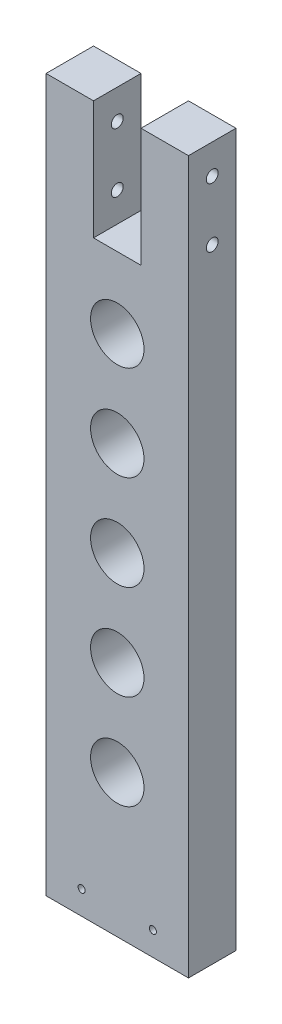
SolidWorks part; units mm, degrees
material "Kiefer"
ref_plane "Ebene vorne" through (0, 0, 0) normal (0, 0, 1) x (1, 0, 0)
ref_plane "Ebene oben" through (0, 0, 0) normal (0, 1, 0) x (1, 0, 0)
ref_plane "Ebene rechts" through (0, 0, 0) normal (1, 0, 0) x (0, 0, -1)
sketch "Skizze1" plane through (0, 0, 0) normal (0, 1, 0) x (1, 0, 0)
  line L1 (-30, 10) -> (30, 10)
  line L2 (-30, 10) -> (-30, -10)
  line L3 (-30, -10) -> (30, -10)
  line L4 (30, 10) -> (30, -10)
  line L5 (-30, 10) -> (30, -10) construction
  line L6 (-30, -10) -> (30, 10) construction
  point P0 (0, 0)
  dimension "D1" = 60
  dimension "D2" = 20
extrude "Aufsatz-Linear austragen1" add sketch "Skizze1" along normal blind 300
sketch "Skizze2" plane through (0, 0, 10) normal (0, 0, 1) x (1, 0, 0)
  line L0 (-30, 300) -> (30, 300) construction
  line L1 (-10, 300) -> (10, 300)
  line L2 (-10, 300) -> (-10, 250)
  line L3 (-10, 250) -> (10, 250)
  line L4 (10, 300) -> (10, 250)
  point P6 (0, 300)
  dimension "D1" = 20
  dimension "D2" = 50
extrude "Schnitt-Linear austragen1" cut sketch "Skizze2" against normal through all
sketch "Skizze3" plane through (0, 0, 10) normal (0, 0, 1) x (1, 0, 0)
  line L0 (0, 0) -> (0, 220) construction
  line L1 (-10, 250) -> (10, 250) construction
  circle A0 centre (0, 220) radius 11.25
  circle A1 centre (0, 180) radius 11.25
  circle A2 centre (0, 140) radius 11.25
  circle A3 centre (0, 100) radius 11.25
  circle A4 centre (0, 60) radius 11.25
  dimension "D1" = 22.5
  dimension "D2" = 30
  dimension "D3" = 40
  dimension "D4" = 80
  dimension "D5" = 120
  dimension "D6" = 160
extrude "Schnitt-Linear austragen2" cut sketch "Skizze3" against normal blind 300
sketch "Skizze7" plane through (0, 0, 10) normal (0, 0, 1) x (1, 0, 0)
  line L0 (-30, 300) -> (-30, 0) construction
  line L1 (-30, 20) -> (0, 20) construction
  line L2 (-30, 20) -> (-30, 0) construction
  line L3 (-30, 0) -> (0, 0) construction
  line L4 (0, 20) -> (0, 0) construction
  line L5 (-30, 20) -> (0, 0) construction
  line L6 (-30, 0) -> (0, 20) construction
  line L8 (30, 0) -> (0, 0) construction
  line L9 (30, 0) -> (30, 20) construction
  line L10 (30, 20) -> (0, 20) construction
  line L11 (0, 0) -> (0, 20) construction
  line L12 (30, 0) -> (0, 20) construction
  line L13 (30, 20) -> (0, 0) construction
  line L15 (-30, 40) -> (-30, 20) construction
  line L16 (-30, 20) -> (0, 20) construction
  line L20 (30, 20) -> (0, 20) construction
  line L21 (30, 20) -> (30, 40) construction
  circle A0 centre (-15, 10) radius 1.5
  circle A1 centre (15, 10) radius 1.5
  point P4 (-15, 10)
  point P11 (15, 10)
  dimension "D2" = 3
  dimension "D1" = 20
extrude "Schnitt-Linear austragen6" cut sketch "Skizze7" against normal through all
sketch "Skizze10" plane through (-10, 0, 0) normal (1, 0, 0) x (0, 0, -1)
  line L0 (10, 300) -> (10, 250) construction
  line L1 (-10, 250) -> (10, 250) construction
  line L2 (-10, 250) -> (-10, 275) construction
  line L3 (-10, 275) -> (10, 275) construction
  line L4 (10, 250) -> (10, 275) construction
  line L5 (-10, 250) -> (10, 275) construction
  line L6 (-10, 275) -> (10, 250) construction
  line L8 (10, 275) -> (-10, 275) construction
  line L9 (10, 275) -> (10, 300) construction
  line L10 (10, 300) -> (-10, 300) construction
  line L11 (-10, 275) -> (-10, 300) construction
  line L12 (10, 275) -> (-10, 300) construction
  line L13 (10, 300) -> (-10, 275) construction
  circle A0 centre (0, 262.5) radius 2.5
  circle A1 centre (0, 287.5) radius 2.5
  point P4 (0, 262.5)
  point P10 (0, 287.5)
  dimension "D1" = 5
extrude "Schnitt-Linear austragen8" cut sketch "Skizze10" against normal through all both and the other way through all
